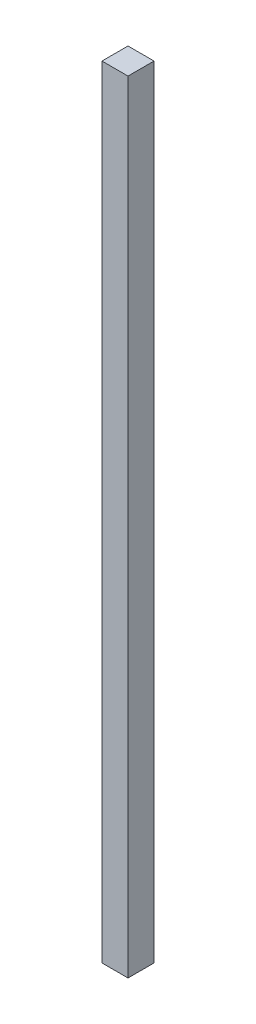
SolidWorks part; units mm, degrees
ref_plane "Front Plane" through (0, 0, 0) normal (0, 0, 1) x (1, 0, 0)
ref_plane "Top Plane" through (0, 0, 0) normal (0, 1, 0) x (1, 0, 0)
ref_plane "Right Plane" through (0, 0, 0) normal (1, 0, 0) x (0, 0, -1)
sketch "Sketch1" plane through (0, 0, 0) normal (0, 1, 0) x (1, 0, 0)
  line L1 (0, 0) -> (20, 0)
  line L2 (0, 0) -> (0, -20)
  line L3 (0, -20) -> (20, -20)
  line L4 (20, 0) -> (20, -20)
extrude "Boss-Extrude1" add sketch "Sketch1" along normal blind 600
